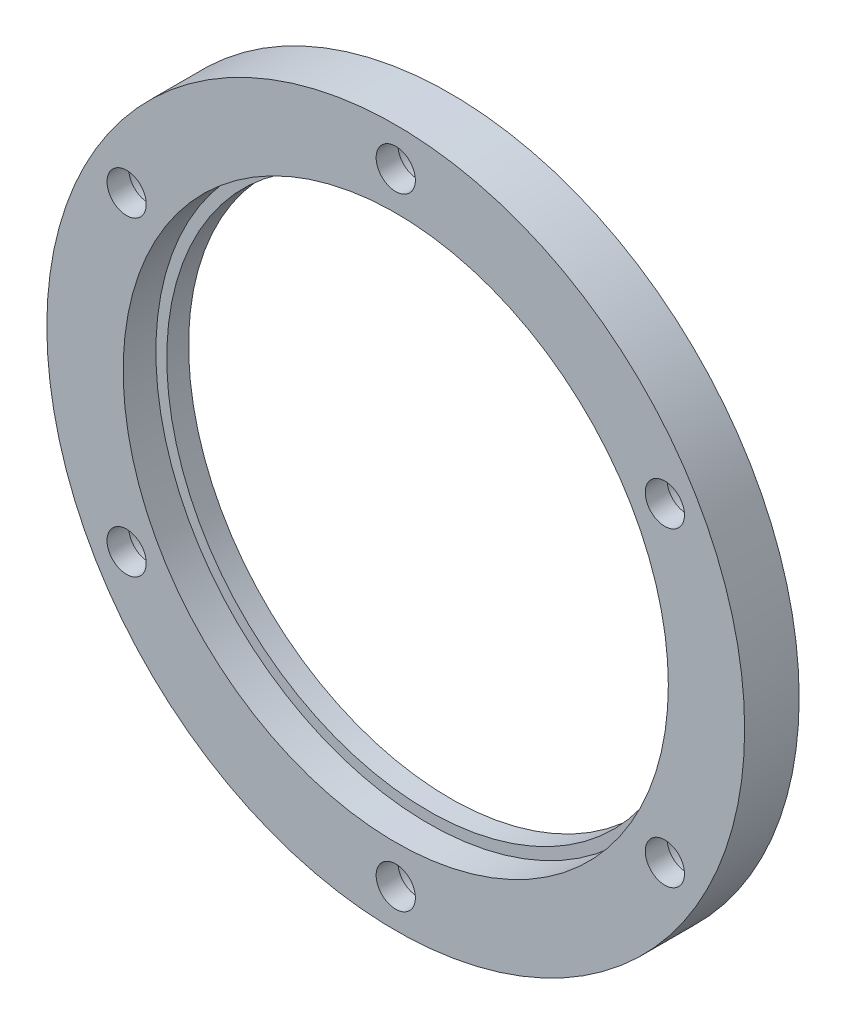
SolidWorks part; units mm, degrees
ref_plane "前视基准面" through (0, 0, 0) normal (0, 0, 1) x (1, 0, 0)
ref_plane "上视基准面" through (0, 0, 0) normal (0, 1, 0) x (1, 0, 0)
ref_plane "右视基准面" through (0, 0, 0) normal (1, 0, 0) x (0, 0, -1)
other "Configuration Table"
sketch "草图1" plane through (0, 0, 0) normal (0, 0, 1) x (1, 0, 0)
  circle A0 centre (0, 0) radius 24
  circle A1 centre (0, 0) radius 32
  dimension "D1" = 48
  dimension "D2" = 64
extrude "凸台-拉伸1" add sketch "草图1" along normal blind 2
sketch "草图2" plane through (0, 0, 2) normal (0, 0, 1) x (1, 0, 0)
  circle A0 centre (0, 0) radius 25
  circle A2 centre (0, 0) radius 32
  circle A3 centre (0, 0) radius 32 construction
  dimension "D1" = 50
extrude "凸台-拉伸2" add sketch "草图2" along normal blind 4
sketch "草图3" plane through (0, 0, 6) normal (0, 0, 1) x (1, 0, 0)
  circle A0 centre (0, 0) radius 28.5 construction
  circle A1 centre (0, 28.5) radius 1.8
  circle A2 centre (24.6817, 14.25) radius 1.8
  circle A3 centre (24.6817, -14.25) radius 1.8
  circle A4 centre (0, -28.5) radius 1.8
  circle A5 centre (-24.6817, -14.25) radius 1.8
  circle A6 centre (-24.6817, 14.25) radius 1.8
  point P17 (0, 0)
  dimension "D1" = 57
  dimension "D2" = 3.6
  dimension "D3" = 6
extrude "切除-拉伸1" cut sketch "草图3" against normal through all
sketch "草图4" plane through (0, 0, 0) normal (0, 0, -1) x (-1, 0, 0)
  circle A0 centre (-24.6817, -14.25) radius 2.85
  circle A1 centre (-24.6817, 14.25) radius 2.85
  circle A2 centre (0, 28.5) radius 2.85
  circle A3 centre (24.6817, 14.25) radius 2.85
  circle A4 centre (24.6817, -14.25) radius 2.85
  circle A5 centre (0, -28.5) radius 2.85
  point P15 (0, 0)
  dimension "D1" = 5.7
  dimension "D2" = 6
extrude "切除-拉伸2" cut sketch "草图4" against normal blind 3
sketch "草图5" plane through (0, 0, 6) normal (0, 0, 1) x (1, 0, 0)
  circle A0 centre (0, 0) radius 25 construction
  circle A1 centre (0, 0) radius 32
  circle A2 centre (0, 0) radius 32
  circle A3 centre (0, 0) radius 25
  circle A4 centre (-24.6817, 14.25) radius 1.8 construction
  circle A5 centre (-24.6817, 14.25) radius 1.8
  circle A6 centre (0, 28.5) radius 1.8
  circle A7 centre (24.6817, 14.25) radius 1.8
  circle A8 centre (24.6817, -14.25) radius 1.8
  circle A9 centre (0, -28.5) radius 1.8
  circle A10 centre (-24.6817, -14.25) radius 1.8
  point P21 (0, 0)
  dimension "D2" = 6
  dimension "D1" = 0
extrude "切除-拉伸3" cut sketch "草图5" against normal blind 1
